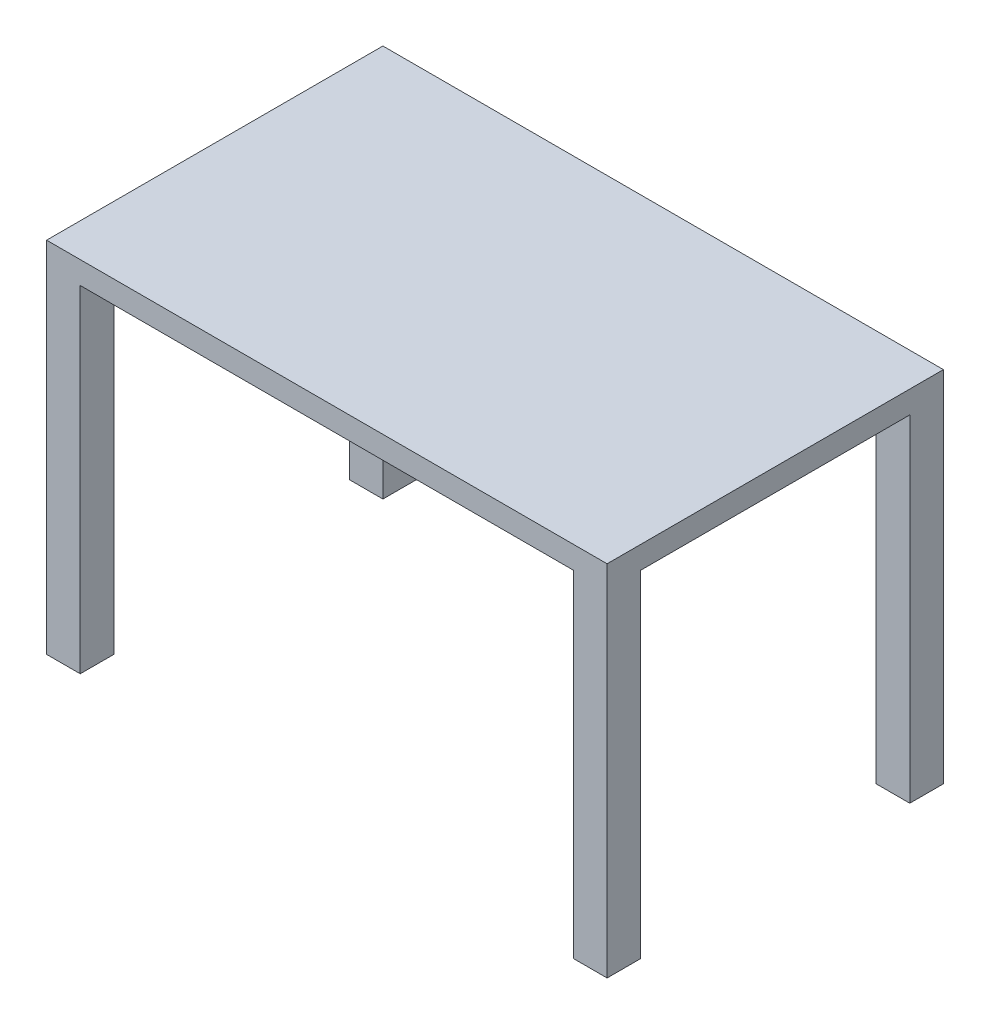
SolidWorks part; units mm, degrees
ref_plane "Front" through (0, 0, 0) normal (0, 0, 1) x (1, 0, 0)
ref_plane "Top" through (0, 0, 0) normal (0, 1, 0) x (1, 0, 0)
ref_plane "Right" through (0, 0, 0) normal (1, 0, 0) x (0, 0, -1)
sketch "Sketch1" plane through (0, 0, 0) normal (0, 1, 0) x (1, 0, 0)
  line L1 (-125, -75) -> (125, -75)
  line L2 (-125, -75) -> (-125, 75)
  line L3 (-125, 75) -> (125, 75)
  line L4 (125, -75) -> (125, 75)
  line L5 (-125, -75) -> (125, 75) construction
  line L6 (-125, 75) -> (125, -75) construction
  point P0 (0, 0)
  dimension "D1" = 250
  dimension "D2" = 150
extrude "Boss-Extrude1" add sketch "Sketch1" along normal blind 10
sketch "Sketch4" plane through (0, 0, 0) normal (0, -1, 0) x (1, 0, 0)
  line L0 (125, 0) -> (-125, 0) construction
  line L1 (125, -75) -> (110, -75)
  line L2 (125, -75) -> (125, -60)
  line L3 (125, -60) -> (110, -60)
  line L4 (110, -75) -> (110, -60)
  line L5 (125, 75) -> (125, -75) construction
  line L6 (-125, -75) -> (-125, 75) construction
  line L7 (0, 75) -> (0, -75) construction
  line L8 (-125, 75) -> (125, 75) construction
  line L9 (125, -75) -> (-125, -75) construction
  line L10 (110, 75) -> (110, 60)
  line L11 (125, 60) -> (110, 60)
  line L12 (125, 75) -> (125, 60)
  line L13 (125, 75) -> (110, 75)
  line L14 (-125, 75) -> (-110, 75)
  line L15 (-125, 75) -> (-125, 60)
  line L16 (-125, 60) -> (-110, 60)
  line L17 (-110, 75) -> (-110, 60)
  line L18 (-110, -75) -> (-110, -60)
  line L19 (-125, -60) -> (-110, -60)
  line L20 (-125, -75) -> (-125, -60)
  line L21 (-125, -75) -> (-110, -75)
  dimension "D1" = 15
extrude "Boss-Extrude2" add sketch "Sketch4" along normal blind 150
